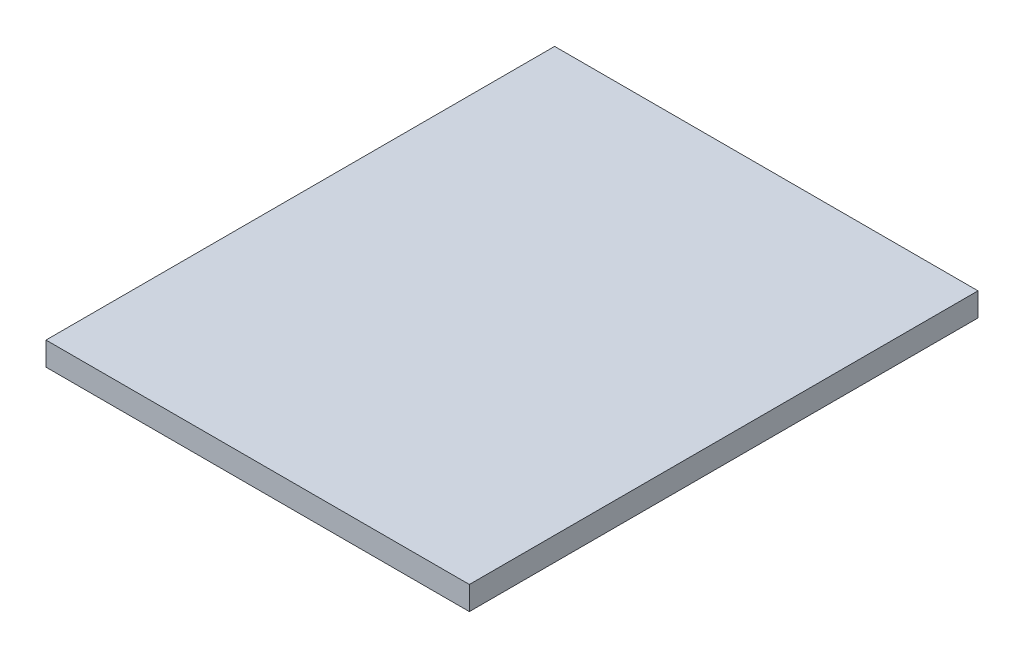
SolidWorks part; units mm, degrees
ref_plane "Front Plane" through (0, 0, 0) normal (0, 0, 1) x (1, 0, 0)
ref_plane "Top Plane" through (0, 0, 0) normal (0, 1, 0) x (1, 0, 0)
ref_plane "Right Plane" through (0, 0, 0) normal (1, 0, 0) x (0, 0, -1)
sketch "Sketch1" plane through (0, 0, 0) normal (0, 1, 0) x (1, 0, 0)
  line L1 (-36, -43.25) -> (36, -43.25)
  line L2 (-36, -43.25) -> (-36, 43.25)
  line L3 (-36, 43.25) -> (36, 43.25)
  line L4 (36, -43.25) -> (36, 43.25)
  line L5 (-36, -43.25) -> (36, 43.25) construction
  line L6 (-36, 43.25) -> (36, -43.25) construction
  point P0 (0, 0)
  dimension "D1" = 72
  dimension "D2" = 86.5
extrude "Boss-Extrude1" add sketch "Sketch1" along normal blind 4
